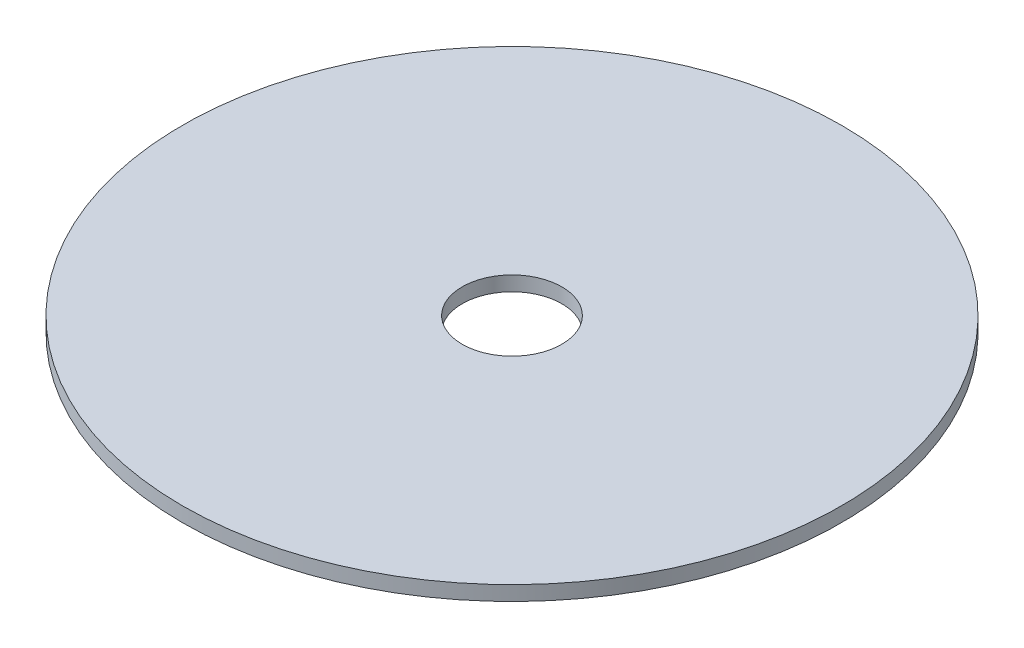
SolidWorks part; units mm, degrees
ref_plane "Alzado" through (0, 0, 0) normal (0, 0, 1) x (1, 0, 0)
ref_plane "Planta" through (0, 0, 0) normal (0, 1, 0) x (1, 0, 0)
ref_plane "Vista lateral" through (0, 0, 0) normal (1, 0, 0) x (0, 0, -1)
sketch "Croquis1" plane through (0, 0, 0) normal (0, 1, 0) x (1, 0, 0)
  circle A0 centre (0, 0) radius 22.5
  circle A1 centre (0, 0) radius 3.4
  dimension "D1" = 45
  dimension "D2" = 6.8
extrude "Saliente-Extruir1" add sketch "Croquis1" along normal blind 1
